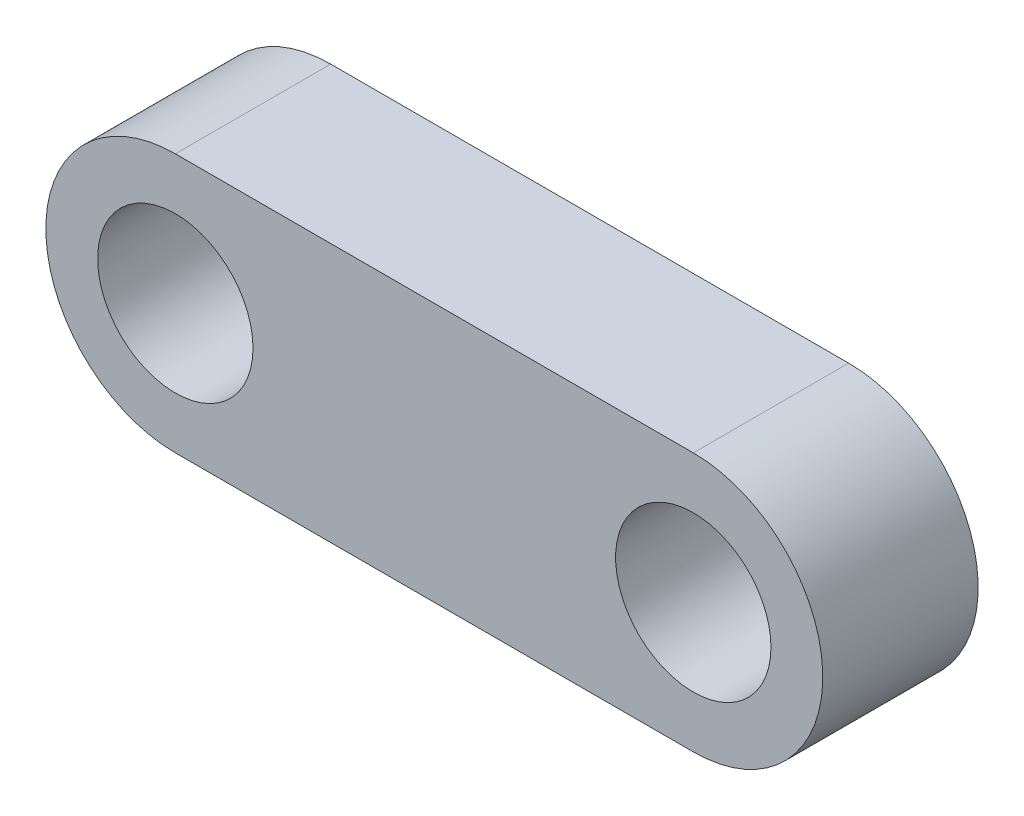
SolidWorks part; units mm, degrees
ref_plane "Plan de face" through (0, 0, 0) normal (0, 0, 1) x (1, 0, 0)
ref_plane "Plan de dessus" through (0, 0, 0) normal (0, 1, 0) x (1, 0, 0)
ref_plane "Plan de droite" through (0, 0, 0) normal (1, 0, 0) x (0, 0, -1)
sketch "Esquisse1" plane through (0, 0, 0) normal (0, 0, 1) x (1, 0, 0)
  line L0 (-5, 0) -> (5, 0) construction
  line L1 (-5, 2.5) -> (5, 2.5)
  line L2 (-5, -2.5) -> (5, -2.5)
  arc A0 (-5, 2.5) -> (-5, -2.5) centre (-5, 0) ccw
  arc A1 (5, -2.5) -> (5, 2.5) centre (5, 0) ccw
  circle A2 centre (-5, 0) radius 1.5
  circle A3 centre (5, 0) radius 1.5
  point P2 (0, 0)
  dimension "D2" = 2.5
  dimension "D1" = 10
extrude "Boss.-Extru.1" add sketch "Esquisse1" along normal blind 3
